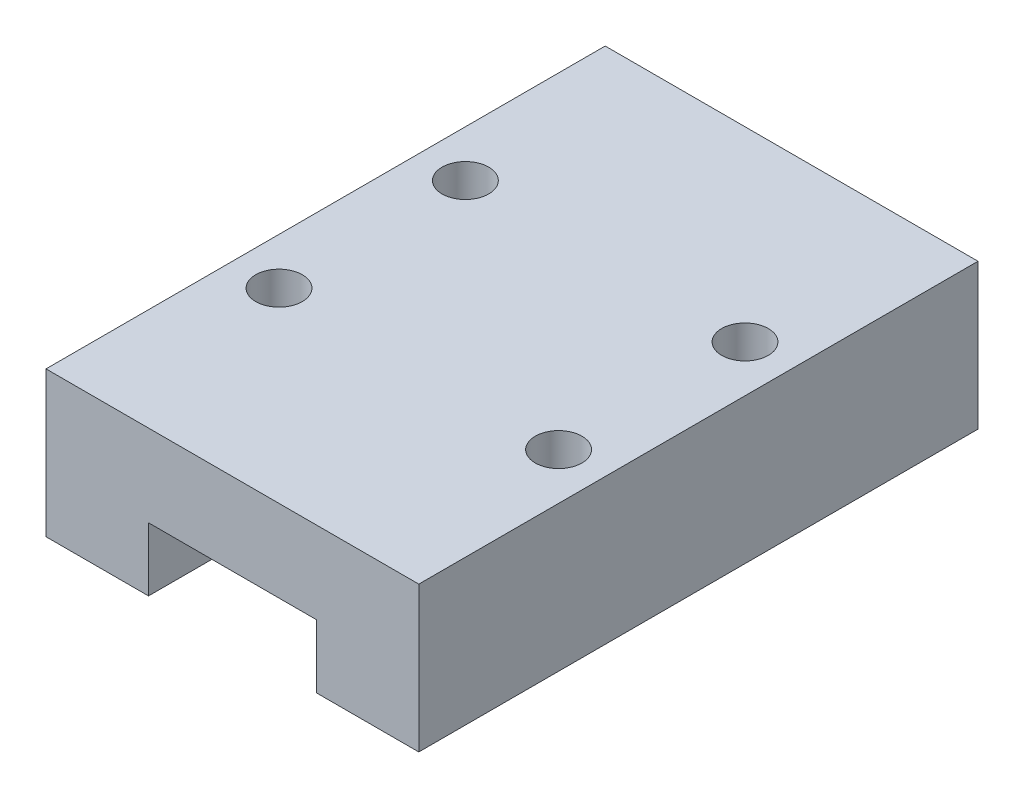
SolidWorks part; units mm, degrees
ref_plane "Plan de face" through (0, 0, 0) normal (0, 0, 1) x (1, 0, 0)
ref_plane "Plan de dessus" through (0, 0, 0) normal (0, 1, 0) x (1, 0, 0)
ref_plane "Plan de droite" through (0, 0, 0) normal (1, 0, 0) x (0, 0, -1)
sketch "Esquisse1" plane through (0, 0, 0) normal (0, 0, 1) x (1, 0, 0)
  line L0 (0, 0) -> (0, 7.8)
  line L1 (0, 7.8) -> (20, 7.8)
  line L2 (20, 7.8) -> (20, 0)
  line L3 (20, 0) -> (14.5, 0)
  line L4 (14.5, 0) -> (14.5, 3.4)
  line L5 (14.5, 3.4) -> (5.5, 3.4)
  line L6 (5.5, 3.4) -> (5.5, 0)
  line L7 (5.5, 0) -> (0, 0)
  dimension "D1" = 7.8
  dimension "D2" = 20
  dimension "D3" = 3.4
  dimension "D4" = 9
extrude "Boss.-Extru.1" add sketch "Esquisse1" along normal blind 30
sketch "Esquisse2" plane through (0, 7.8, 0) normal (0, 1, 0) x (1, 0, 0)
  line L0 (0, -15) -> (20, -15) construction
  line L1 (0, -30) -> (0, 0) construction
  line L2 (20, -30) -> (20, 0) construction
  line L3 (17.5, 0) -> (17.5, -30) construction
  line L4 (20, 0) -> (0, 0) construction
  line L5 (20, -30) -> (0, -30) construction
  line L6 (2.5, -30) -> (2.5, 0) construction
  line L7 (0, -10) -> (20, -10) construction
  line L8 (20, -20) -> (0, -20) construction
  circle A0 centre (2.5, -10) radius 1.25
  circle A1 centre (17.5, -10) radius 1.25
  circle A2 centre (17.5, -20) radius 1.25
  circle A3 centre (2.5, -20) radius 1.25
  dimension "D5" = 2.5
  dimension "D1" = 15
  dimension "D2" = 2.5
  dimension "D3" = 5
  dimension "D4" = 5
extrude "Enlèv. mat.-Extru.1" cut sketch "Esquisse2" against normal blind 2.6
